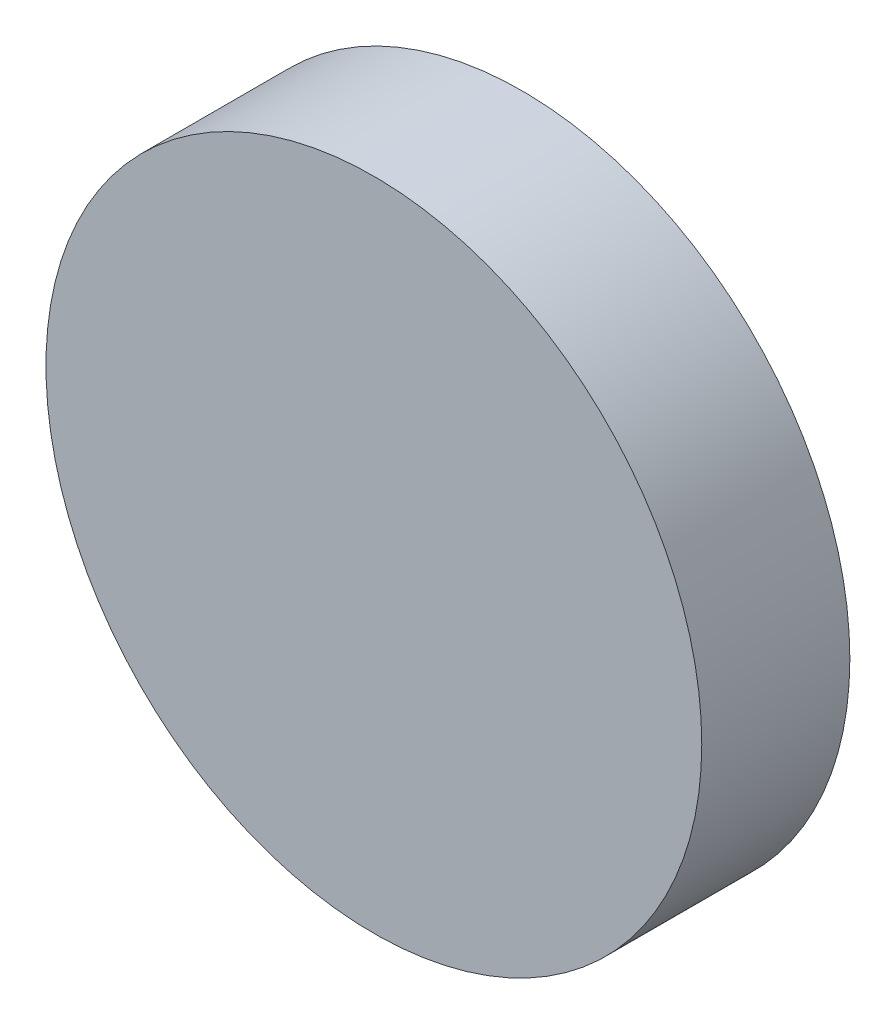
SolidWorks part; units mm, degrees
material "AISI 1020"
ref_plane "Plan de face" through (0, 0, 0) normal (0, 0, 1) x (1, 0, 0)
ref_plane "Plan de dessus" through (0, 0, 0) normal (0, 1, 0) x (1, 0, 0)
ref_plane "Plan de droite" through (0, 0, 0) normal (1, 0, 0) x (0, 0, -1)
sketch "Esquisse1" plane through (0, 0, 0) normal (0, 0, 1) x (1, 0, 0)
  circle A0 centre (0, 0) radius 31
extrude "Boss.-Extru.1" add sketch "Esquisse1" along normal blind 14
sketch "Esquisse2" plane through (0, 0, 0) normal (0, 0, -1) x (-1, 0, 0)
  circle A0 centre (0, 0) radius 22.5
  circle A1 centre (0, 0) radius 12.5
  circle A2 centre (0, 0) radius 31 construction
  dimension "D1" = 45
  dimension "D2" = 25
extrude "Enlèv. mat.-Extru.1" cut sketch "Esquisse2" against normal blind 3
